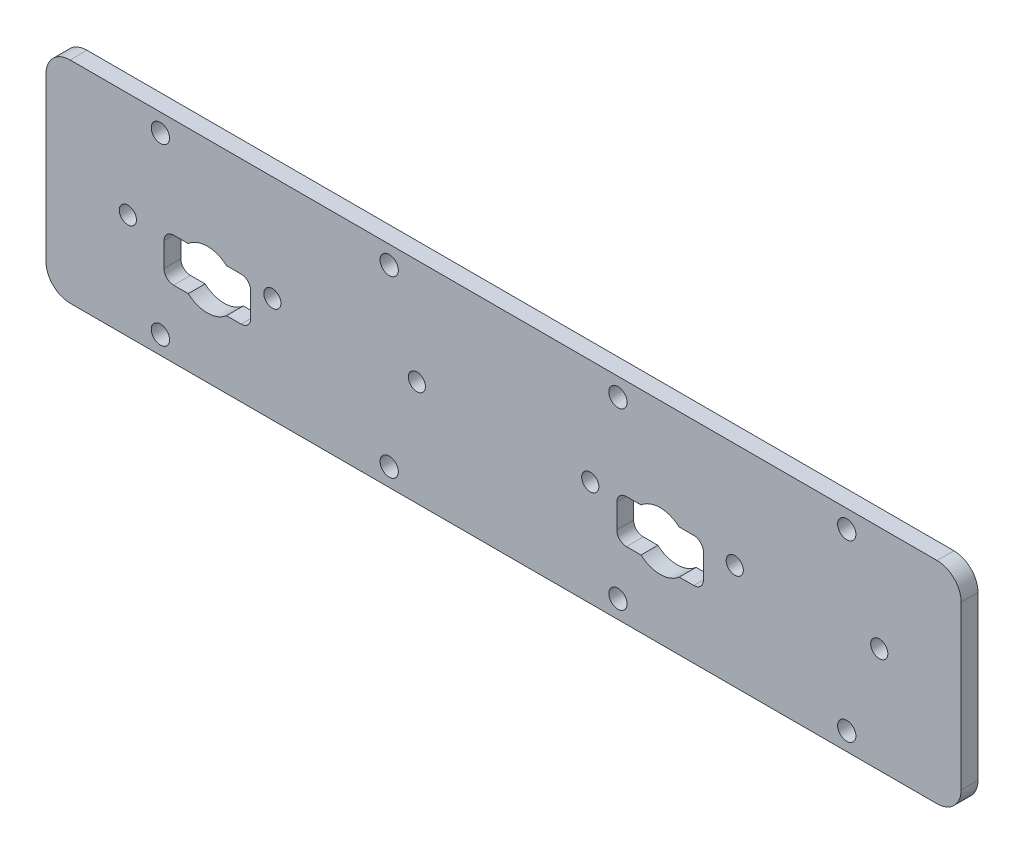
SolidWorks part; units mm, degrees
material "ABS"
ref_plane "Front Plane" through (0, 0, 0) normal (0, 0, 1) x (1, 0, 0)
ref_plane "Top Plane" through (0, 0, 0) normal (0, 1, 0) x (1, 0, 0)
ref_plane "Right Plane" through (0, 0, 0) normal (1, 0, 0) x (0, 0, -1)
sketch "Sketch1" plane through (0, 0, 32) normal (0, 0, 1) x (1, 0, 0)
  line L1 (95, 21.875) -> (-95, 21.875)
  line L2 (95, 21.875) -> (95, -21.875)
  line L3 (95, -21.875) -> (-95, -21.875)
  line L4 (-95, 21.875) -> (-95, -21.875)
extrude "Boss-Extrude1" add sketch "Sketch1" along normal blind 3.5
hole_wizard "#6 Clearance Hole1" positions "Sketch2" profile "Sketch4" hole size "#6" standard "ANSI Inch" end condition through all
sketch "Sketch2" plane through (0, 0, 35.5) normal (0, 0, 1) x (1, 0, 0)
  point P0 (71.25, 18.125)
  point P3 (23.75, 18.125)
  point P6 (-23.75, 18.125)
  point P9 (-71.25, 18.125)
  point P12 (-71.25, -18.125)
  point P15 (-23.75, -18.125)
  point P18 (23.75, -18.125)
  point P21 (71.25, -18.125)
sketch "Sketch4" plane through (71.25, 18.125, 35.5) normal (1, 0, 0) x (0, -1, 0)
  line L0 (0, 0) -> (0, 3.5)
  line L1 (0, 3.5) -> (1.8986, 3.5)
  line L2 (1.8986, 3.5) -> (1.8986, 0)
  line L5 (1.8986, 0) -> (0, 0)
  line L11 (0, -6.35) -> (0, 107.95) construction
  dimension "Thru Hole Dia." = 3.7973
  dimension "Thru Hole Depth" = 3.5
sketch "Sketch6" plane through (0, 0, 35.5) normal (0, 0, 1) x (1, 0, 0)
  line L0 (23.5, -7.875) -> (23.5, 1.125) construction
  line L1 (23.5, -7.875) -> (41.5, -7.875) construction
  line L2 (23.5, 1.125) -> (41.5, 1.125) construction
  line L3 (41.5, -7.875) -> (41.5, 1.125) construction
  line L4 (23.5, -7.875) -> (41.5, 1.125) construction
  line L5 (23.5, 1.125) -> (41.5, -7.875) construction
  line L6 (36.4686, -7.875) -> (41.5, -7.875)
  line L7 (41.5, -7.875) -> (41.5, 1.125)
  line L8 (41.5, 1.125) -> (36.4686, 1.125)
  line L9 (28.5314, 1.125) -> (23.5, 1.125)
  line L10 (23.5, 1.125) -> (23.5, -7.875)
  line L11 (23.5, -7.875) -> (28.5314, -7.875)
  line L12 (-70.5, 1.125) -> (-70.5, -7.875)
  line L13 (-65.4686, 1.125) -> (-70.5, 1.125)
  line L14 (-52.5, 1.125) -> (-57.5314, 1.125)
  line L15 (-52.5, -7.875) -> (-52.5, 1.125)
  line L16 (-57.5314, -7.875) -> (-52.5, -7.875)
  line L17 (-70.5, -7.875) -> (-65.4686, -7.875)
  line L18 (23.5, 1.125) -> (-70.5, 1.125) construction
  circle A0 centre (32.5, -3.375) radius 6 construction
  arc A2 (28.5314, 1.125) -> (36.4686, 1.125) centre (32.5, -3.375) cw
  arc A3 (28.5314, -7.875) -> (36.4686, -7.875) centre (32.5, -3.375) ccw
  arc A4 (-65.4686, 1.125) -> (-57.5314, 1.125) centre (-61.5, -3.375) cw
  arc A5 (-65.4686, -7.875) -> (-57.5314, -7.875) centre (-61.5, -3.375) ccw
  dimension "D1" = 12
  dimension "D2" = 18
  dimension "D3" = 9
  dimension "D5" = 94
  dimension "D4" = 2
extrude "Cut-Extrude1" cut sketch "Sketch6" against normal through all
fillet "Fillet1" radius 2 8 edges at (-70.5, -7.875, 33.75) (-70.5, 1.125, 33.75) (-52.5, -7.875, 33.75) (-52.5, 1.125, 33.75) (23.5, -7.875, 33.75) (23.5, 1.125, 33.75) (41.5, -7.875, 33.75) (41.5, 1.125, 33.75)
fillet "Fillet2" radius 5 4 edges at (-95, -21.875, 33.75) (-95, 21.875, 33.75) (95, 21.875, 33.75) (95, -21.875, 33.75)
sketch "Sketch7" plane through (0, 0, 35.5) normal (0, 0, 1) x (1, 0, 0)
  line L0 (1, 0) -> (95, 0) construction
  line L1 (48, 21.875) -> (48, -21.875) construction
  line L3 (-90, -21.875) -> (90, -21.875) construction
  line L4 (-95, 21.875) -> (95, 21.875) construction
  line L5 (0, 21.875) -> (0, -21.875) construction
  line L7 (90, 21.875) -> (-90, 21.875) construction
  point P0 (78, 0)
  point P5 (48, 0)
  point P9 (-78, 0)
  point P17 (-48, 0)
  point P18 (-18, 0)
  point P19 (18, 0)
  dimension "D1" = 60
hole_wizard "#6 Clearance Hole2" positions "Sketch8" profile "Sketch9" hole size "#6" standard "ANSI Inch" end condition through all
sketch "Sketch8" plane through (0, 0, 35.5) normal (0, 0, 1) x (1, 0, 0)
  line L0 (48, 21.875) -> (48, -21.875) construction
  point P0 (78, 0)
  point P3 (48, 0)
  point P7 (18, 0)
  point P10 (-18, 0)
  point P13 (-48, 0)
  point P16 (-78, 0)
sketch "Sketch9" plane through (78, 0, 35.5) normal (1, 0, 0) x (0, -1, 0)
  line L0 (0, 0) -> (0, 3.5)
  line L1 (0, 3.5) -> (1.778, 3.5)
  line L2 (1.778, 3.5) -> (1.778, 0)
  line L5 (1.778, 0) -> (0, 0)
  line L11 (0, -6.35) -> (0, 107.95) construction
  dimension "Thru Hole Dia." = 3.556
  dimension "Thru Hole Depth" = 3.5
equation "\"wall_thickness\"= 7.5mm"
equation "\"D1@Boss-Extrude1\"=\"wall_thickness\""
